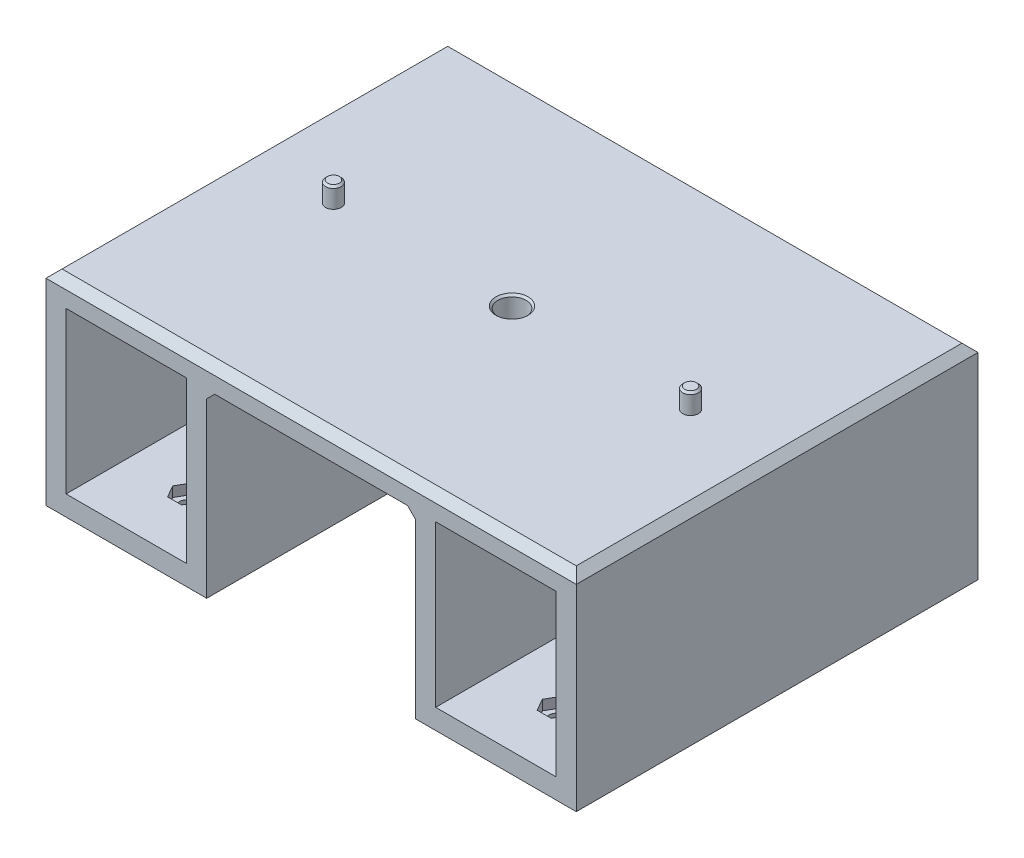
SolidWorks part; units mm, degrees
ref_plane "前视基准面" through (0, 0, 0) normal (0, 0, 1) x (1, 0, 0)
ref_plane "上视基准面" through (0, 0, 0) normal (0, 1, 0) x (1, 0, 0)
ref_plane "右视基准面" through (0, 0, 0) normal (1, 0, 0) x (0, 0, -1)
sketch "草图1" plane through (0, 0, 0) normal (0, 0, 1) x (1, 0, 0)
  line L0 (0, -0.8453) -> (0, 49.0792) construction
  line L1 (-55, 0) -> (-81, 0) construction
  line L2 (55, 0) -> (-55, 0) construction
  line L3 (0, 51) -> (0, 45)
  line L4 (-66, 5) -> (-66, 51)
  line L5 (-66, 51) -> (-60, 51)
  line L6 (-60, 51) -> (0, 51)
  line L7 (0, 45) -> (-26, 45)
  line L8 (-61, 45) -> (-61, 5)
  line L11 (-31, 45) -> (-31, 5)
  line L12 (-31, 5) -> (-66, 5)
  line L13 (-66, 5) -> (-66, 0)
  line L14 (-66, 0) -> (-26, 0)
  line L15 (-26, 0) -> (-26, 45)
  line L16 (-66, 0) -> (-26, 0)
  line L17 (-31, 45) -> (-55, 45)
  line L18 (-61, 45) -> (-55, 45)
  dimension "D1" = 5
  dimension "D2" = 30
  dimension "D3" = 6
  dimension "D4" = 5
  dimension "D5" = 26
  dimension "D6" = 5
  dimension "D9" = 45
extrude "凸台-拉伸1" add sketch "草图1" along normal mid plane 100
mirror "镜向1" about plane through (0, 0, 50) normal (1, 0, 0) of "凸台-拉伸1"
sketch "草图2" plane through (0, 51, 0) normal (0, 1, 0) x (1, 0, 0)
  circle A0 centre (0, 0) radius 3.5
  dimension "D1" = 7
extrude "切除-拉伸1" cut sketch "草图2" against normal through all
sketch "草图3" plane through (0, 51, 0) normal (0, 1, 0) x (1, 0, 0)
  line L0 (-55, 0) -> (55, 0) construction
  line L1 (0, 0) -> (0, 21.0973) construction
  circle A0 centre (44.45, 0) radius 1.95
  circle A1 centre (0, 0) radius 3.5 construction
  circle A2 centre (-44.45, 0) radius 1.95
  dimension "D1" = 3.9
  dimension "D2" = 44.45
extrude "凸台-拉伸2" add sketch "草图3" along normal blind 5
sketch "草图4" plane through (0, 0, 0) normal (0, -1, 0) x (1, 0, 0)
  line L0 (66, 50) -> (26, 50) construction
  line L1 (-46, -35) -> (46, -35) construction
  line L2 (-46, -35) -> (-46, 35) construction
  line L3 (-46, 35) -> (46, 35) construction
  line L4 (46, -35) -> (46, 35) construction
  line L5 (0, 35) -> (0, -35) construction
  line L6 (-46, 0) -> (46, 0) construction
  line L8 (-46, 50) -> (-46, 40.4325) construction
  line L9 (-66, 50) -> (-26, 50) construction
  circle A0 centre (-46, 35) radius 1.75
  circle A1 centre (46, 35) radius 1.75
  circle A2 centre (46, -35) radius 1.75
  circle A3 centre (-46, -35) radius 1.75
  point P0 (0, 0)
  dimension "D1" = 3.5
  dimension "D2" = 15
extrude "切除-拉伸2" cut sketch "草图4" against normal up to next
chamfer "倒角1" distance 2 angle 45 2 edges at (26, 45, 0) (-26, 45, 0)
chamfer "倒角2" distance 2 angle 45 4 edges at (66, 51, 0) (0, 51, -50) (0, 51, 50) (-66, 51, 0)
chamfer "倒角3" distance 0.5 angle 45 3 edges at (0, 51, 3.5) (44.45, 56, 1.95) (-44.45, 56, -1.95)
sketch "草图6" plane through (0, 5, 0) normal (0, 1, 0) x (1, 0, 0)
  line L0 (-30.8, 0) -> (30.8, 0) construction
  line L1 (42.5359, 35) -> (44.2679, 32)
  line L2 (44.2679, 32) -> (47.7321, 32)
  line L3 (47.7321, 32) -> (49.4641, 35)
  line L4 (49.4641, 35) -> (47.7321, 38)
  line L5 (47.7321, 38) -> (44.2679, 38)
  line L6 (44.2679, 38) -> (42.5359, 35)
  line L7 (-47.7321, 32) -> (-44.2679, 32)
  line L8 (-44.2679, 32) -> (-42.5359, 35)
  line L9 (-42.5359, 35) -> (-44.2679, 38)
  line L10 (-44.2679, 38) -> (-47.7321, 38)
  line L11 (-47.7321, 38) -> (-49.4641, 35)
  line L12 (-49.4641, 35) -> (-47.7321, 32)
  line L13 (-47.7321, -38) -> (-44.2679, -38)
  line L14 (-44.2679, -38) -> (-42.5359, -35)
  line L15 (-42.5359, -35) -> (-44.2679, -32)
  line L16 (-44.2679, -32) -> (-47.7321, -32)
  line L17 (-47.7321, -32) -> (-49.4641, -35)
  line L18 (-49.4641, -35) -> (-47.7321, -38)
  line L19 (42.5359, -35) -> (44.2679, -38)
  line L20 (44.2679, -38) -> (47.7321, -38)
  line L21 (47.7321, -38) -> (49.4641, -35)
  line L22 (49.4641, -35) -> (47.7321, -32)
  line L23 (47.7321, -32) -> (44.2679, -32)
  line L24 (44.2679, -32) -> (42.5359, -35)
  circle A0 centre (46, 35) radius 3 construction
  circle A1 centre (-46, 35) radius 3 construction
  circle A2 centre (-46, -35) radius 3 construction
  circle A3 centre (46, -35) radius 3 construction
  dimension "D1" = 6
extrude "切除-拉伸3" cut sketch "草图6" against normal blind 2.5
